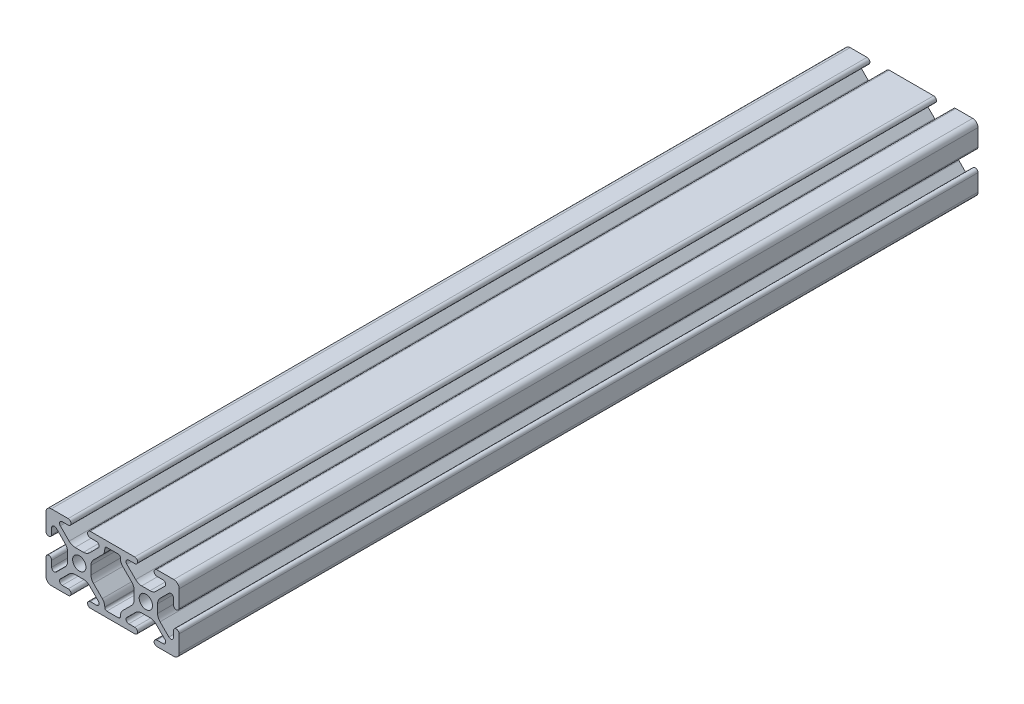
SolidWorks part; units mm, degrees
ref_plane "Front Plane" through (0, 0, 0) normal (0, 0, 1) x (1, 0, 0)
ref_plane "Top Plane" through (0, 0, 0) normal (0, 1, 0) x (1, 0, 0)
ref_plane "Right Plane" through (0, 0, 0) normal (1, 0, 0) x (0, 0, -1)
sketch "Sketch1" plane through (0, 0, 0) normal (0, 0, 1) x (1, 0, 0)
  line L0 (9.57, -9.3582) -> (9.5625, -9.6)
  line L1 (9.5632, 9.5764) -> (9.57, 9.3582)
  line L2 (-12.5, 10.5) -> (-12.5, 4.1733)
  line L3 (-10.36, 4.1733) -> (-10.36, 6.4282)
  line L4 (-8.6498, 7.1366) -> (-5.3285, 3.8153)
  line L5 (-4.4, 1.5737) -> (-4.4, -1.5737)
  line L6 (-5.3285, -3.8153) -> (-8.6498, -7.1366)
  line L7 (-10.36, -6.4282) -> (-10.36, -4.1733)
  line L8 (-12.5, -4.1733) -> (-12.5, -10.5)
  line L9 (-10.5, -12.5) -> (-4.1733, -12.5)
  line L10 (-4.1733, -10.36) -> (-6.4282, -10.36)
  line L11 (-7.1366, -8.6498) -> (-3.8153, -5.3285)
  line L12 (-1.5737, -4.4) -> (1.5737, -4.4)
  line L13 (3.8153, -5.3285) -> (7.1366, -8.6498)
  line L14 (6.4282, -10.36) -> (4.1733, -10.36)
  line L15 (4.1733, -12.5) -> (20.8267, -12.5)
  line L16 (8.6498, -7.1366) -> (5.3285, -3.8153)
  line L17 (4.4, -1.5737) -> (4.4, 1.5737)
  line L18 (5.3285, 3.8153) -> (8.6498, 7.1366)
  line L19 (20.8267, 12.5) -> (4.1733, 12.5)
  line L20 (4.1733, 10.36) -> (6.4282, 10.36)
  line L21 (7.1366, 8.6498) -> (3.8153, 5.3285)
  line L22 (1.5737, 4.4) -> (-1.5737, 4.4)
  line L23 (-3.8153, 5.3285) -> (-7.1366, 8.6498)
  line L24 (-6.4282, 10.36) -> (-4.1733, 10.36)
  line L25 (-4.1733, 12.5) -> (-10.5, 12.5)
  line L26 (15.43, -9.3582) -> (15.4368, -9.5764)
  line L27 (15.4368, 9.5764) -> (15.43, 9.3582)
  line L28 (37.5, 10.5) -> (37.5, 4.1733)
  line L29 (35.36, 4.1733) -> (35.36, 6.4282)
  line L30 (33.6498, 7.1366) -> (30.3285, 3.8153)
  line L31 (29.4, 1.5737) -> (29.4, -1.5737)
  line L32 (30.3285, -3.8153) -> (33.6498, -7.1366)
  line L33 (35.36, -6.4282) -> (35.36, -4.1733)
  line L34 (37.5, -4.1733) -> (37.5, -10.5)
  line L35 (35.5, -12.5) -> (29.1733, -12.5)
  line L36 (29.1733, -10.36) -> (31.4282, -10.36)
  line L37 (32.1366, -8.6498) -> (28.8153, -5.3285)
  line L38 (26.5737, -4.4) -> (23.4263, -4.4)
  line L39 (21.1847, -5.3285) -> (17.8634, -8.6498)
  line L40 (18.5718, -10.36) -> (20.8267, -10.36)
  line L41 (16.3502, -7.1366) -> (19.6715, -3.8153)
  line L42 (20.6, -1.5737) -> (20.6, 1.5737)
  line L43 (19.6715, 3.8153) -> (16.3502, 7.1366)
  line L44 (20.8267, 10.36) -> (18.5718, 10.36)
  line L45 (17.8634, 8.6498) -> (21.1847, 5.3285)
  line L46 (23.4263, 4.4) -> (26.5737, 4.4)
  line L47 (28.8153, 5.3285) -> (32.1366, 8.6498)
  line L48 (31.4282, 10.36) -> (29.1733, 10.36)
  line L49 (29.1733, 12.5) -> (35.5, 12.5)
  line L50 (14.6771, -10.36) -> (10.3225, -10.36)
  line L51 (10.3229, 10.36) -> (14.6771, 10.36)
  arc A0 (8.6498, 7.1366) -> (9.57, 9.3582) centre (6.4282, 9.3582) ccw
  arc A1 (9.564, -9.5529) -> (8.6498, -7.1366) centre (6.4282, -9.3582) ccw
  circle A2 centre (0, 0) radius 2.5
  arc A3 (-12.5, 4.1733) -> (-10.36, 4.1733) centre (-11.43, 4.1733) ccw
  arc A4 (-8.6498, 7.1366) -> (-10.36, 6.4282) centre (-9.3582, 6.4282) ccw
  arc A5 (-4.4, 1.5737) -> (-5.3285, 3.8153) centre (-7.57, 1.5737) ccw
  arc A6 (-5.3285, -3.8153) -> (-4.4, -1.5737) centre (-7.57, -1.5737) ccw
  arc A7 (-10.36, -6.4282) -> (-8.6498, -7.1366) centre (-9.3582, -6.4282) ccw
  arc A8 (-10.36, -4.1733) -> (-12.5, -4.1733) centre (-11.43, -4.1733) ccw
  arc A9 (-4.1733, -12.5) -> (-4.1733, -10.36) centre (-4.1733, -11.43) ccw
  arc A10 (-7.1366, -8.6498) -> (-6.4282, -10.36) centre (-6.4282, -9.3582) ccw
  arc A11 (-1.5737, -4.4) -> (-3.8153, -5.3285) centre (-1.5737, -7.57) ccw
  arc A12 (3.8153, -5.3285) -> (1.5737, -4.4) centre (1.5737, -7.57) ccw
  arc A13 (6.4282, -10.36) -> (7.1366, -8.6498) centre (6.4282, -9.3582) ccw
  arc A14 (4.1733, -10.36) -> (4.1733, -12.5) centre (4.1733, -11.43) ccw
  arc A15 (4.4, -1.5737) -> (5.3285, -3.8153) centre (7.57, -1.5737) ccw
  arc A16 (5.3285, 3.8153) -> (4.4, 1.5737) centre (7.57, 1.5737) ccw
  arc A17 (4.1733, 12.5) -> (4.1733, 10.36) centre (4.1733, 11.43) ccw
  arc A18 (7.1366, 8.6498) -> (6.4282, 10.36) centre (6.4282, 9.3582) ccw
  arc A19 (1.5737, 4.4) -> (3.8153, 5.3285) centre (1.5737, 7.57) ccw
  arc A20 (-3.8153, 5.3285) -> (-1.5737, 4.4) centre (-1.5737, 7.57) ccw
  arc A21 (-6.4282, 10.36) -> (-7.1366, 8.6498) centre (-6.4282, 9.3582) ccw
  arc A22 (-4.1733, 10.36) -> (-4.1733, 12.5) centre (-4.1733, 11.43) ccw
  arc A23 (-10.5, 12.5) -> (-12.5, 10.5) centre (-10.5, 10.5) ccw
  arc A24 (-12.5, -10.5) -> (-10.5, -12.5) centre (-10.5, -10.5) ccw
  arc A25 (15.43, 9.3582) -> (16.3502, 7.1366) centre (18.5718, 9.3582) ccw
  arc A26 (16.3502, -7.1366) -> (15.43, -9.3582) centre (18.5718, -9.3582) ccw
  circle A27 centre (25, 0) radius 2.5
  arc A28 (35.36, 4.1733) -> (37.5, 4.1733) centre (36.43, 4.1733) ccw
  arc A29 (35.36, 6.4282) -> (33.6498, 7.1366) centre (34.3582, 6.4282) ccw
  arc A30 (30.3285, 3.8153) -> (29.4, 1.5737) centre (32.57, 1.5737) ccw
  arc A31 (29.4, -1.5737) -> (30.3285, -3.8153) centre (32.57, -1.5737) ccw
  arc A32 (33.6498, -7.1366) -> (35.36, -6.4282) centre (34.3582, -6.4282) ccw
  arc A33 (37.5, -4.1733) -> (35.36, -4.1733) centre (36.43, -4.1733) ccw
  arc A34 (35.5, -12.5) -> (37.5, -10.5) centre (35.5, -10.5) ccw
  arc A35 (29.1733, -10.36) -> (29.1733, -12.5) centre (29.1733, -11.43) ccw
  arc A36 (31.4282, -10.36) -> (32.1366, -8.6498) centre (31.4282, -9.3582) ccw
  arc A37 (28.8153, -5.3285) -> (26.5737, -4.4) centre (26.5737, -7.57) ccw
  arc A38 (23.4263, -4.4) -> (21.1847, -5.3285) centre (23.4263, -7.57) ccw
  arc A39 (17.8634, -8.6498) -> (18.5718, -10.36) centre (18.5718, -9.3582) ccw
  arc A40 (20.8267, -12.5) -> (20.8267, -10.36) centre (20.8267, -11.43) ccw
  arc A41 (19.6715, -3.8153) -> (20.6, -1.5737) centre (17.43, -1.5737) ccw
  arc A42 (20.6, 1.5737) -> (19.6715, 3.8153) centre (17.43, 1.5737) ccw
  arc A43 (20.8267, 10.36) -> (20.8267, 12.5) centre (20.8267, 11.43) ccw
  arc A44 (18.5718, 10.36) -> (17.8634, 8.6498) centre (18.5718, 9.3582) ccw
  arc A45 (21.1847, 5.3285) -> (23.4263, 4.4) centre (23.4263, 7.57) ccw
  arc A46 (26.5737, 4.4) -> (28.8153, 5.3285) centre (26.5737, 7.57) ccw
  arc A47 (32.1366, 8.6498) -> (31.4282, 10.36) centre (31.4282, 9.3582) ccw
  arc A48 (29.1733, 12.5) -> (29.1733, 10.36) centre (29.1733, 11.43) ccw
  arc A49 (37.5, 10.5) -> (35.5, 12.5) centre (35.5, 10.5) ccw
  arc A50 (9.564, -9.5529) -> (10.3225, -10.36) centre (10.3225, -9.6) ccw
  arc A51 (14.6771, -10.36) -> (15.4368, -9.5764) centre (14.6771, -9.6) ccw
  arc A52 (10.3229, 10.36) -> (9.5632, 9.5764) centre (10.3229, 9.6) ccw
  arc A53 (15.4368, 9.5764) -> (14.6771, 10.36) centre (14.6771, 9.6) ccw
extrude "Extrude1" add sketch "Sketch1" against normal blind 300 contours L28 A49 L49 A48 L48 A47 L47 A46 L46 A45 L45 A44 L44 A43 L19 A17 L20 A18 L21 A19 L22 A20 L23 A21 L24 A22 L25 A23 L2 A3 L3 A4 L4 A5 L5 A6 L6 A7 L7 A8 L8 A24 L9 A9 L10 A10 L11 A11 L12 A12 L13
